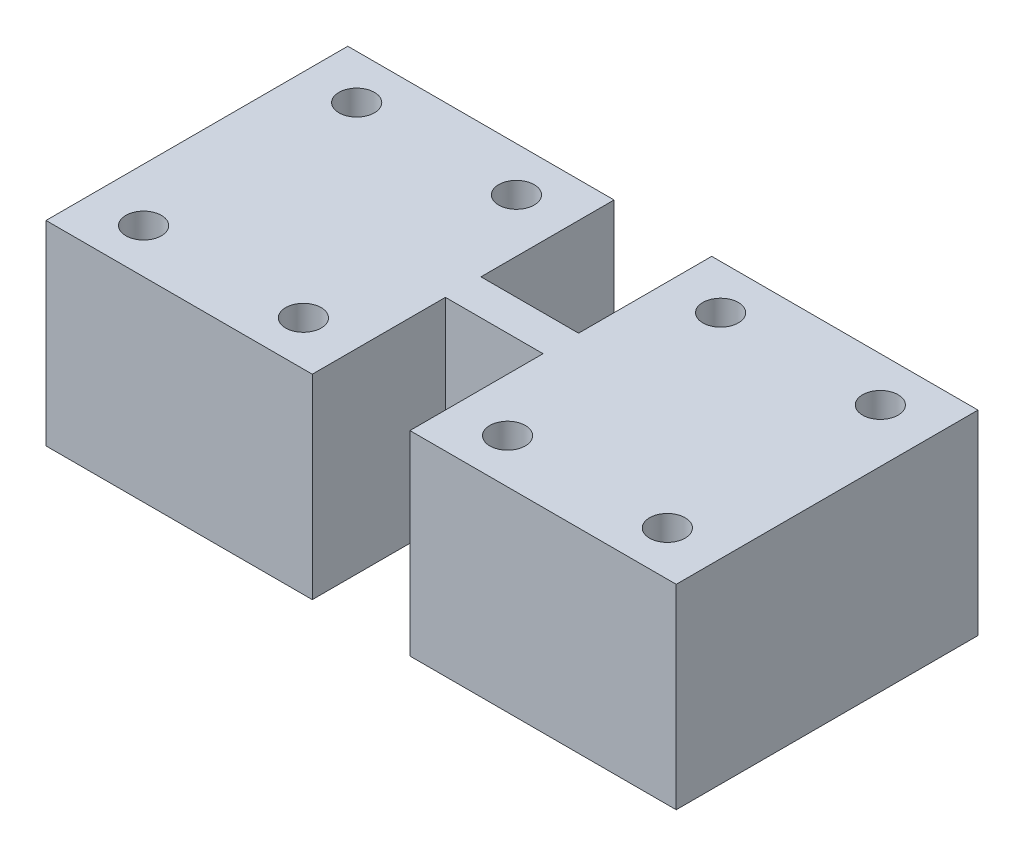
SolidWorks part; units mm, degrees
ref_plane "前视基准面" through (0, 0, 0) normal (0, 0, 1) x (1, 0, 0)
ref_plane "上视基准面" through (0, 0, 0) normal (0, 1, 0) x (1, 0, 0)
ref_plane "右视基准面" through (0, 0, 0) normal (1, 0, 0) x (0, 0, -1)
sketch "草图1" plane through (0, 0, 0) normal (0, 1, 0) x (1, 0, 0)
  line L0 (0, 0) -> (0, 34)
  line L1 (0, 34) -> (30, 34)
  line L2 (30, 34) -> (30, 19)
  line L3 (30, 0) -> (0, 0)
  line L4 (0, 17) -> (-50000, 17) construction
  line L5 (15, 34) -> (15, -49966) construction
  line L6 (30, 19) -> (41, 19)
  line L8 (30, 15) -> (41, 15)
  line L13 (30, 15) -> (30, 0)
  line L14 (41, 0) -> (41, 15)
  line L15 (41, 34) -> (71, 34)
  line L16 (71, 34) -> (71, 0)
  line L17 (71, 0) -> (41, 0)
  line L18 (41, 19) -> (41, 34)
  line L19 (56, 34) -> (56, -49966) construction
  circle A0 centre (6, 29) radius 2
  circle A1 centre (24, 29) radius 2
  circle A2 centre (24, 5) radius 2
  circle A3 centre (6, 5) radius 2
  circle A8 centre (47, 29) radius 2
  circle A12 centre (47, 5) radius 2
  circle A13 centre (65, 5) radius 2
  circle A14 centre (65, 29) radius 2
  point P10 (0, 17)
  point P12 (15, 34)
  point P23 (41, 17)
  point P32 (56, 34)
  dimension "D3" = 4
  dimension "D9" = 34
  dimension "D10" = 4
  dimension "D1" = 30
  dimension "D2" = 34
  dimension "D4" = 5
  dimension "D5" = 6
  dimension "D6" = 11
  dimension "D7" = 2
  dimension "D8" = 30
  dimension "D11" = 5
  dimension "D12" = 6
extrude "凸台-拉伸1" add sketch "草图1" along normal blind 22
